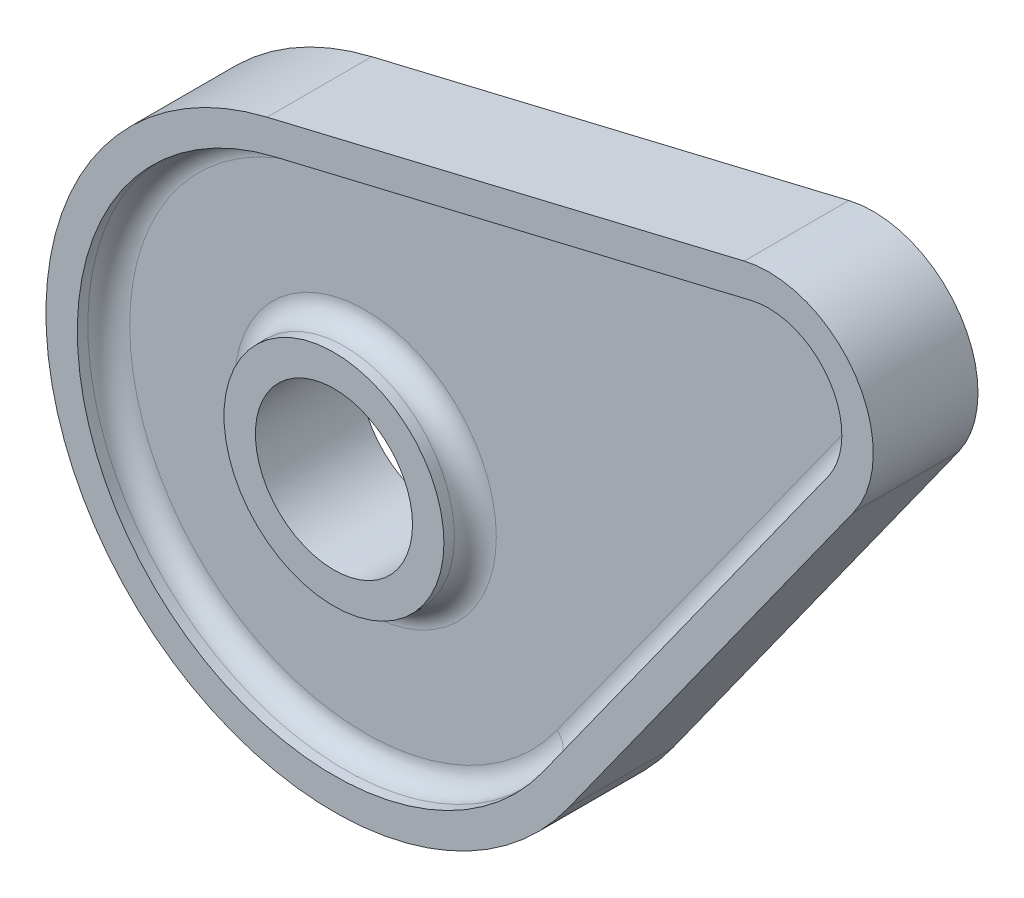
SolidWorks part; units mm, degrees
ref_plane "Front Plane" through (0, 0, 0) normal (0, 0, 1) x (1, 0, 0)
ref_plane "Top Plane" through (0, 0, 0) normal (0, 1, 0) x (1, 0, 0)
ref_plane "Right Plane" through (0, 0, 0) normal (1, 0, 0) x (0, 0, -1)
ref_plane "Plane1" through (0, 0, 13) normal (0, 0, 1) x (1, 0, 0)
sketch "Sketch2" plane through (0, 0, 13) normal (0, 0, 1) x (1, 0, 0)
  line L0 (-18.5097, 27.9026) -> (-60, 0) construction
  line L1 (-20.8329, 37.629) -> (-66.3889, 26.7476)
  line L2 (-37.6374, -16.0051) -> (-10.3778, 22.0826)
  arc A0 (-66.3889, 26.7476) -> (-37.6374, -16.0051) centre (-60, 0) ccw
  arc A1 (-10.3778, 22.0826) -> (-20.8329, 37.629) centre (-18.5097, 27.9026) ccw
  circle A4 centre (-60, 0) radius 7.5
  point P9 (-18.3476, 28.0116)
  dimension "D1" = 55
  dimension "D2" = 20
  dimension "D3" = 50
extrude "Boss-Extrude1" add sketch "Sketch2" along normal blind 10
sketch "Sketch3" plane through (0, 0, 23) normal (0, 0, 1) x (1, 0, 0)
  line L0 (-20.8329, 37.629) -> (-66.3889, 26.7476) construction
  line L1 (-37.6374, -16.0051) -> (-10.3778, 22.0826) construction
  line L10 (-20.8329, 37.629) -> (-66.3889, 26.7476)
  line L11 (-37.6374, -16.0051) -> (-10.3778, 22.0826)
  line L12 (-40.0769, -14.2591) -> (-12.8174, 23.8286)
  line L13 (-20.136, 34.7111) -> (-65.6919, 23.8296)
  circle A0 centre (-60, 0) radius 7.5 construction
  arc A1 (-10.3778, 22.0826) -> (-20.8329, 37.629) centre (-18.5097, 27.9026) ccw construction
  arc A2 (-66.3889, 26.7476) -> (-37.6374, -16.0051) centre (-60, 0) ccw construction
  circle A15 centre (-60, 0) radius 7.5
  arc A16 (-10.3778, 22.0826) -> (-20.8329, 37.629) centre (-18.5097, 27.9026) ccw
  arc A17 (-66.3889, 26.7476) -> (-37.6374, -16.0051) centre (-60, 0) ccw
  arc A18 (-12.8174, 23.8286) -> (-20.136, 34.7111) centre (-18.5097, 27.9026) ccw
  arc A19 (-65.6919, 23.8296) -> (-40.0769, -14.2591) centre (-60, 0) ccw
  circle A21 centre (-60, 0) radius 10.5
  dimension "D1" = 3
  dimension "D2" = 3
extrude "Cut-Extrude1" cut sketch "Sketch3" against normal blind 3 contours L13 A19 L12 A18 A21
sketch "Sketch4" plane through (0, 0, 13) normal (0, 0, -1) x (-1, 0, 0)
  line L2 (65.6919, 23.8296) -> (20.136, 34.7111)
  line L3 (12.8174, 23.8286) -> (40.0769, -14.2591)
  line L4 (65.6919, 23.8296) -> (20.136, 34.7111)
  line L5 (12.8174, 23.8286) -> (40.0769, -14.2591)
  circle A0 centre (60, 0) radius 10.5 construction
  circle A1 centre (60, 0) radius 10.5
  arc A2 (40.0769, -14.2591) -> (65.6919, 23.8296) centre (60, 0) ccw
  arc A3 (20.136, 34.7111) -> (12.8174, 23.8286) centre (18.5097, 27.9026) ccw
  arc A4 (40.0769, -14.2591) -> (65.6919, 23.8296) centre (60, 0) ccw
  arc A5 (20.136, 34.7111) -> (12.8174, 23.8286) centre (18.5097, 27.9026) ccw
  dimension "D1" = 0
extrude "Cut-Extrude2" cut sketch "Sketch4" against normal blind 3
fillet "Fillet1" radius 2 10 edges at (-12.7011, 31.809, 20) (-26.4472, 4.7848, 20) (-80.3302, -13.6723, 20) (-42.9139, 29.2704, 20) (-49.5, 0, 20) (-42.9139, 29.2704, 16) (-80.3302, -13.6723, 16) (-26.4472, 4.7848, 16) (-12.7011, 31.809, 16) (-70.5, 0, 16)
